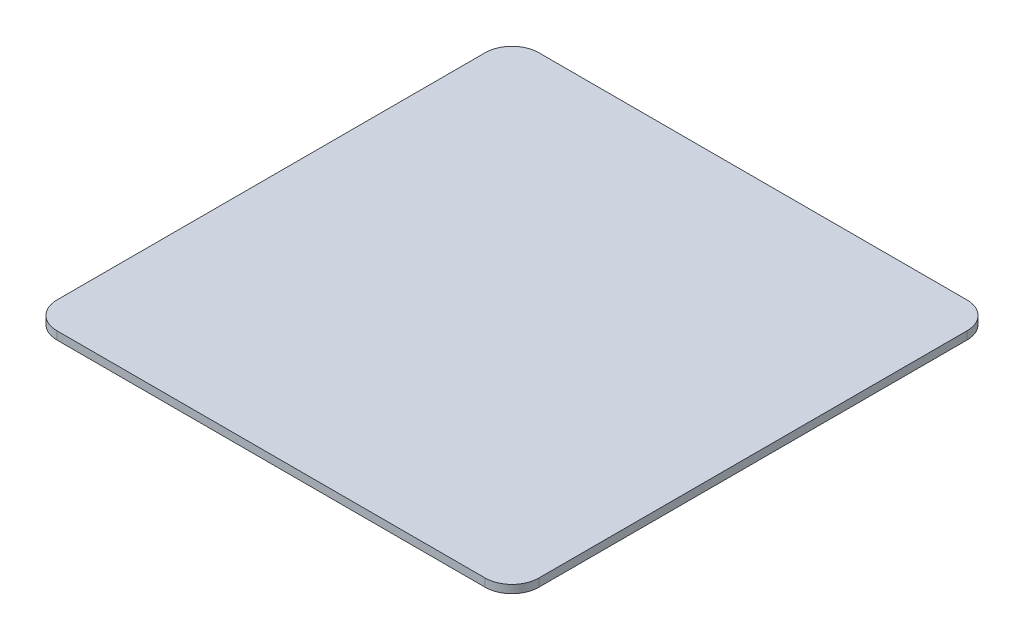
SolidWorks part; units mm, degrees
ref_plane "Front Plane" through (0, 0, 0) normal (0, 0, 1) x (1, 0, 0)
ref_plane "Top Plane" through (0, 0, 0) normal (0, 1, 0) x (1, 0, 0)
ref_plane "Right Plane" through (0, 0, 0) normal (1, 0, 0) x (0, 0, -1)
sketch "Sketch1" plane through (0, 0, 0) normal (0, 1, 0) x (1, 0, 0)
  line L1 (-90, 90) -> (90, 90)
  line L2 (-90, 90) -> (-90, -90)
  line L3 (-90, -90) -> (90, -90)
  line L4 (90, 90) -> (90, -90)
  line L5 (-90, 90) -> (90, -90) construction
  line L6 (-90, -90) -> (90, 90) construction
  point P0 (0, 0)
  dimension "D1" = 180
  dimension "D2" = 180
extrude "Boss-Extrude1" add sketch "Sketch1" along normal blind 3
fillet "Fillet1" radius 10 4 edges at (90, 1.5, -90) (90, 1.5, 90) (-90, 1.5, 90) (-90, 1.5, -90)
